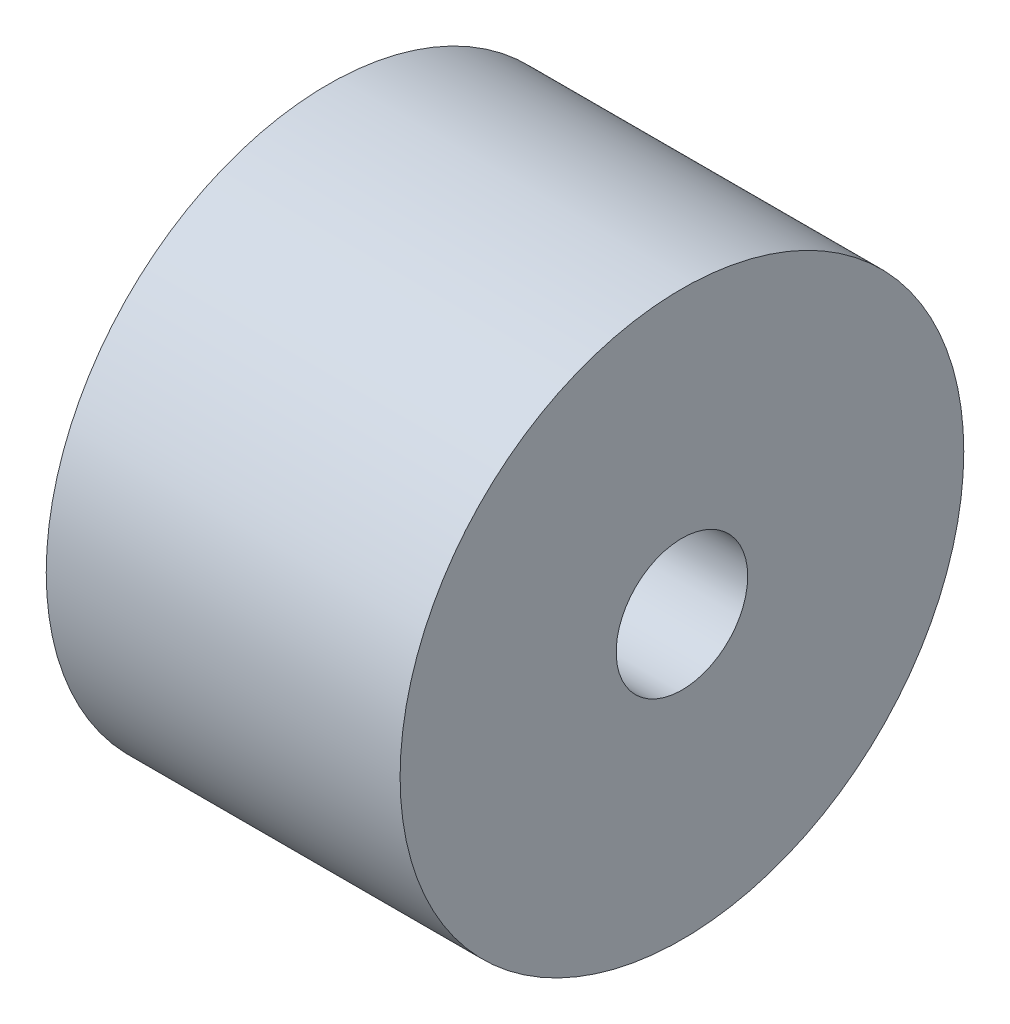
SolidWorks part; units mm, degrees
ref_plane "Front Plane" through (0, 0, 0) normal (0, 0, 1) x (1, 0, 0)
ref_plane "Top Plane" through (0, 0, 0) normal (0, 1, 0) x (1, 0, 0)
ref_plane "Right Plane" through (0, 0, 0) normal (1, 0, 0) x (0, 0, -1)
sketch "Sketch1" plane through (0, 0, 0) normal (1, 0, 0) x (0, 0, -1)
  circle A0 centre (0, 0) radius 2.1
  circle A1 centre (0, 0) radius 9
  dimension "D1" = 4.2
  dimension "D2" = 18
extrude "Boss-Extrude1" add sketch "Sketch1" along normal blind 11.3
